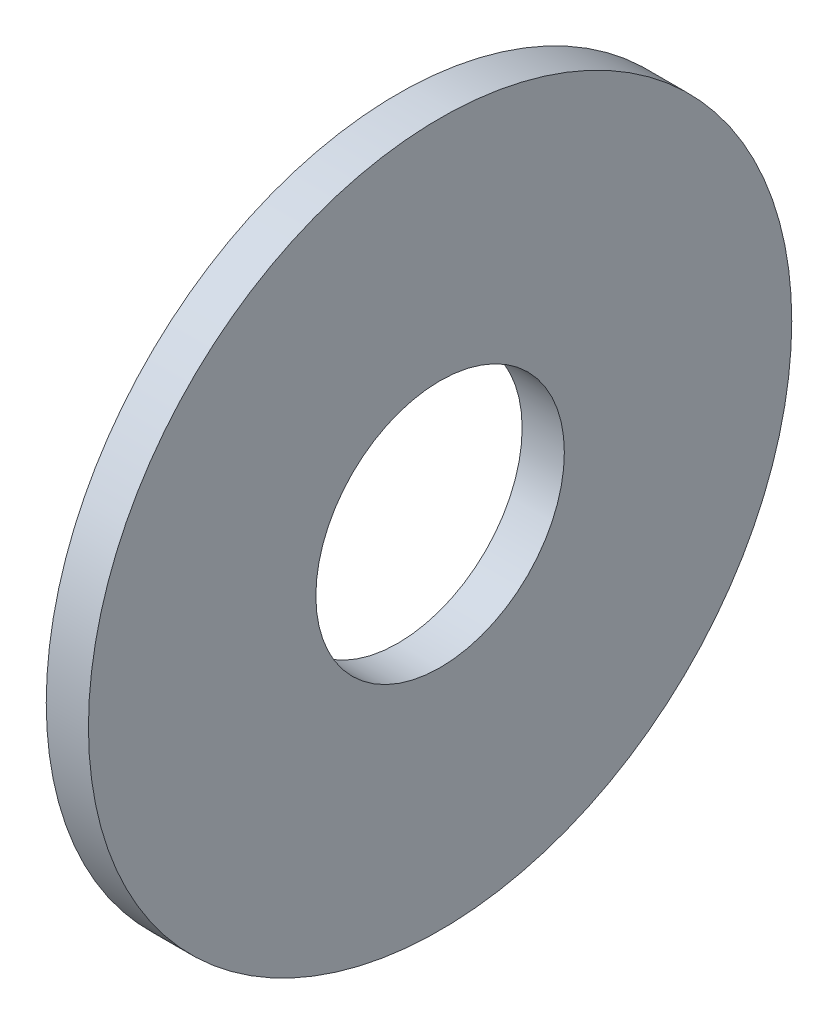
SolidWorks part; units mm, degrees
ref_plane "Front Plane" through (0, 0, 0) normal (0, 0, 1) x (1, 0, 0)
ref_plane "Top Plane" through (0, 0, 0) normal (0, 1, 0) x (1, 0, 0)
ref_plane "Right Plane" through (0, 0, 0) normal (1, 0, 0) x (0, 0, -1)
sketch "Sketch1" plane through (0, 0, 0) normal (1, 0, 0) x (0, 0, -1)
  circle A0 centre (0, 0) radius 9.525
  circle A1 centre (0, 0) radius 3.3655
  dimension "OD" = 19.05
  dimension "ID" = 6.731
extrude "Boss-Extrude1" add sketch "Sketch1" along normal blind 1.143
